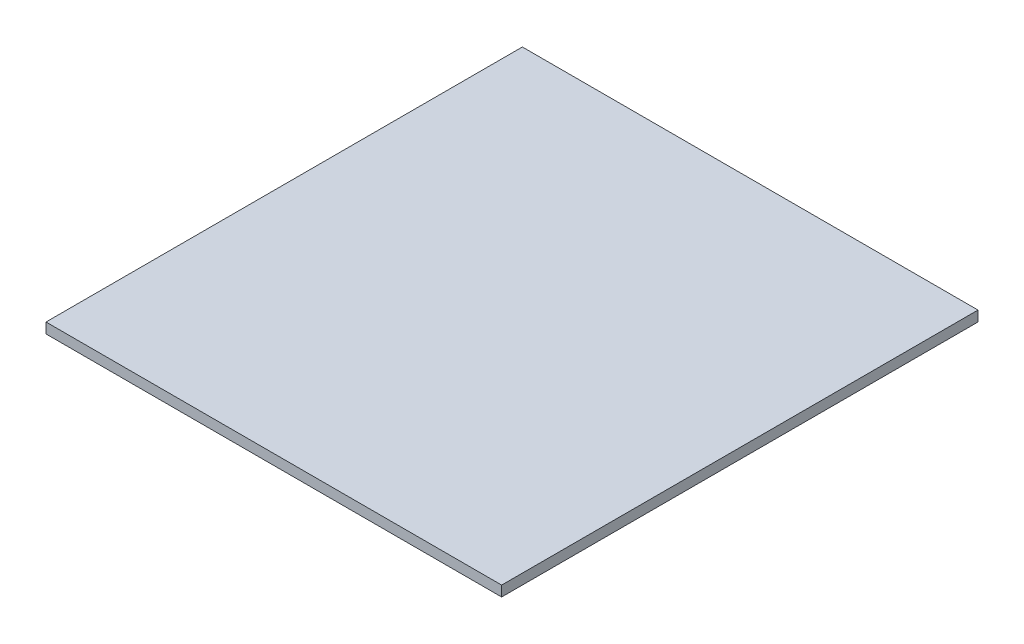
SolidWorks part; units mm, degrees
ref_plane "Front Plane" through (0, 0, 0) normal (0, 0, 1) x (1, 0, 0)
ref_plane "Top Plane" through (0, 0, 0) normal (0, 1, 0) x (1, 0, 0)
ref_plane "Right Plane" through (0, 0, 0) normal (1, 0, 0) x (0, 0, -1)
sketch "Sketch1" plane through (0, 0, 0) normal (0, 1, 0) x (1, 0, 0)
  line L1 (0, 0) -> (279.4, 0)
  line L2 (0, 0) -> (0, 292.1)
  line L3 (0, 292.1) -> (279.4, 292.1)
  line L4 (279.4, 0) -> (279.4, 292.1)
  dimension "D1" = 279.4
  dimension "D2" = 292.1
extrude "Boss-Extrude1" add sketch "Sketch1" along normal blind 6.35
